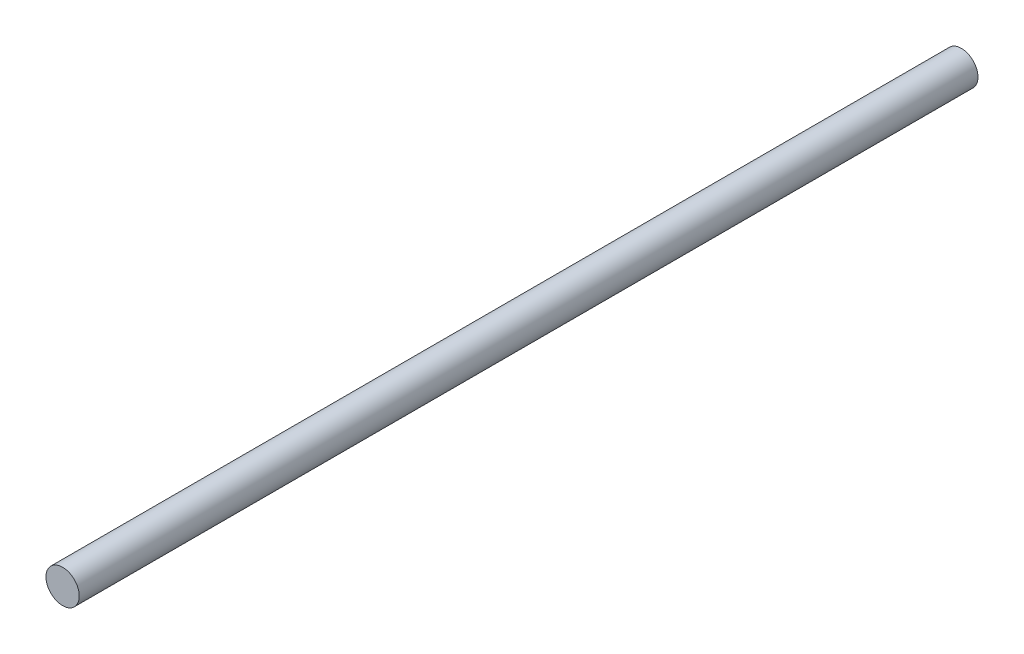
SolidWorks part; units mm, degrees
ref_plane "前视基准面" through (0, 0, 0) normal (0, 0, 1) x (1, 0, 0)
ref_plane "上视基准面" through (0, 0, 0) normal (0, 1, 0) x (1, 0, 0)
ref_plane "右视基准面" through (0, 0, 0) normal (1, 0, 0) x (0, 0, -1)
sketch "草图1" plane through (0, 0, 0) normal (0, 0, 1) x (1, 0, 0)
  circle A0 centre (0, 0) radius 3
  dimension "D1" = 6
extrude "凸台-拉伸1" add sketch "草图1" along normal blind 162
